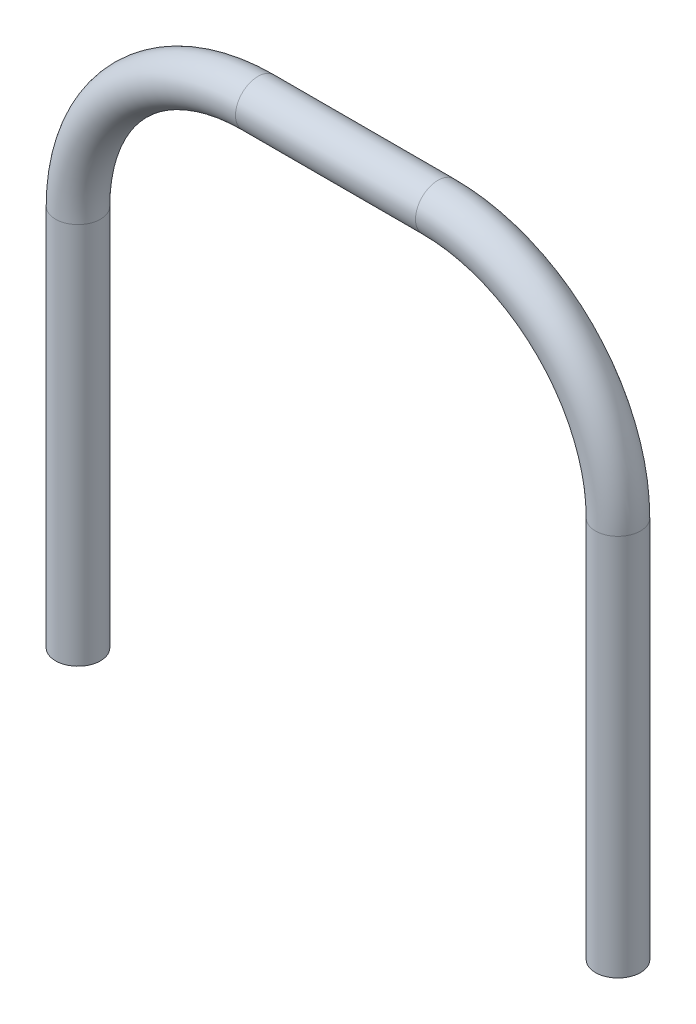
SolidWorks part; units mm, degrees
ref_plane "Front Plane" through (0, 0, 0) normal (0, 0, 1) x (1, 0, 0)
ref_plane "Top Plane" through (0, 0, 0) normal (0, 1, 0) x (1, 0, 0)
ref_plane "Right Plane" through (0, 0, 0) normal (1, 0, 0) x (0, 0, -1)
sketch "Sketch1" plane through (0, 0, 0) normal (0, 0, 1) x (1, 0, 0)
  line L0 (0, 0) -> (0, 431.8)
  line L1 (203.2, 635) -> (406.4, 635)
  line L2 (609.6, 431.8) -> (609.6, 0)
  arc A0 (203.2, 635) -> (0, 431.8) centre (203.2, 431.8) ccw
  arc A1 (406.4, 635) -> (609.6, 431.8) centre (406.4, 431.8) cw
  point P7 (0, 635)
  point P10 (609.6, 635)
  dimension "D4" = 203.2
  dimension "D1" = 609.6
  dimension "D2" = 635
  dimension "D3" = 635
  dimension "D5" = 431.8
sketch "Sketch2" plane through (0, 0, 0) normal (0, 1, 0) x (1, 0, 0)
  circle A0 centre (0, 0) radius 25.4
  dimension "D1" = 50.8
sweep "Sweep1" add profiles "Sketch2" path "Sketch1"
sketch "Sketch3" plane through (0, 0, 0) normal (0, -1, 0) x (1, 0, 0)
  circle A0 centre (0, 0) radius 23.749
  circle A1 centre (0, 0) radius 25.4 construction
  dimension "D1" = 1.651
extrude "Cut-Extrude1" cut sketch "Sketch3" against normal blind 363.22
sketch "Sketch4" plane through (0, 0, 0) normal (0, -1, 0) x (1, 0, 0)
  circle A0 centre (609.6, 0) radius 23.749
  circle A1 centre (609.6, 0) radius 25.4 construction
  dimension "D1" = 1.651
extrude "Cut-Extrude2" cut sketch "Sketch4" against normal blind 401.32
